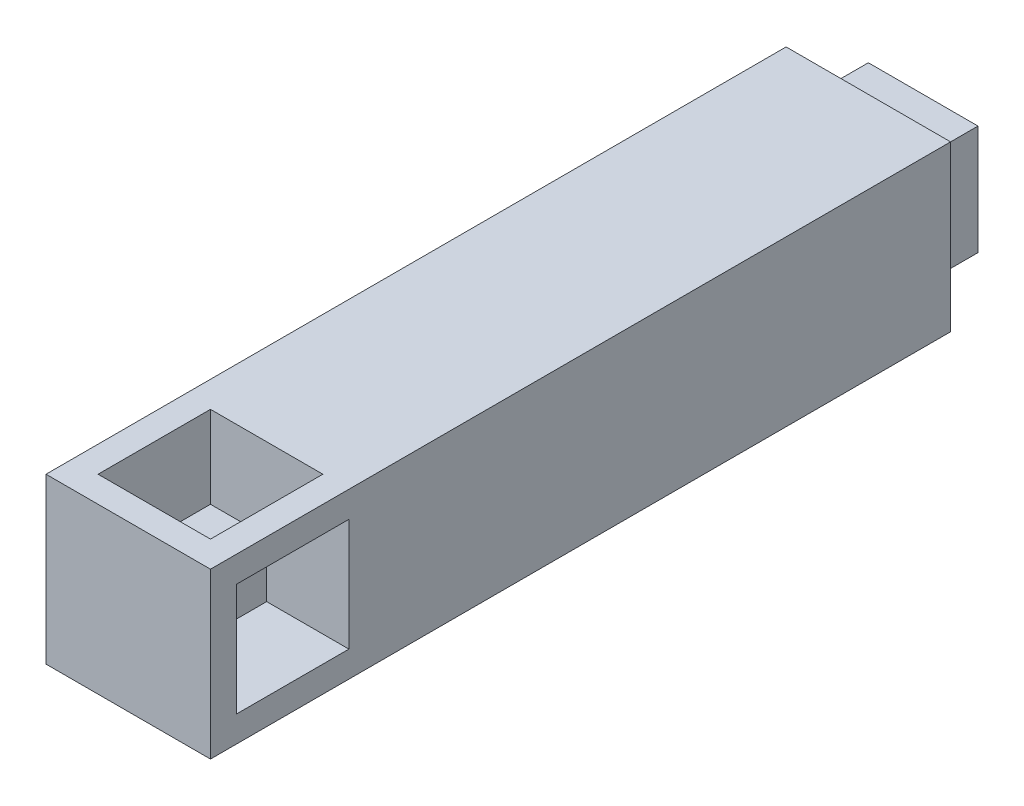
SolidWorks part; units mm, degrees
ref_plane "Front Plane" through (0, 0, 0) normal (0, 0, 1) x (1, 0, 0)
ref_plane "Top Plane" through (0, 0, 0) normal (0, 1, 0) x (1, 0, 0)
ref_plane "Right Plane" through (0, 0, 0) normal (1, 0, 0) x (0, 0, -1)
sketch "Sketch1" plane through (0, 0, 0) normal (0, 0, 1) x (1, 0, 0)
  line L1 (-15, -15) -> (15, -15)
  line L2 (-15, -15) -> (-15, 15)
  line L3 (-15, 15) -> (15, 15)
  line L4 (15, -15) -> (15, 15)
extrude "Boss-Extrude1" add sketch "Sketch1" along normal blind 135
sketch "Sketch2" plane through (0, 0, 0) normal (0, 0, 1) x (1, 0, 0)
  line L1 (-10, -10) -> (10, -10)
  line L2 (-10, -10) -> (-10, 10)
  line L3 (-10, 10) -> (10, 10)
  line L4 (10, -10) -> (10, 10)
extrude "Boss-Extrude2" add sketch "Sketch2" against normal blind 10
sketch "Sketch3" plane through (15, 0, 0) normal (1, 0, 0) x (0, 0, -1)
  line L0 (-130.25, -10.25) -> (-109.75, -10.25)
  line L1 (-109.75, -10.25) -> (-109.75, 10.25)
  line L2 (-109.75, 10.25) -> (-130.25, 10.25)
  line L3 (-130.25, 10.25) -> (-130.25, -10.25)
extrude "Cut-Extrude1" cut sketch "Sketch3" against normal blind 15
sketch "Sketch4" plane through (0, 15, 0) normal (0, 1, 0) x (1, 0, 0)
  line L0 (-10.25, -130.25) -> (10.25, -130.25)
  line L1 (10.25, -130.25) -> (10.25, -109.75)
  line L2 (10.25, -109.75) -> (-10.25, -109.75)
  line L3 (-10.25, -109.75) -> (-10.25, -130.25)
extrude "Cut-Extrude2" cut sketch "Sketch4" against normal blind 15
